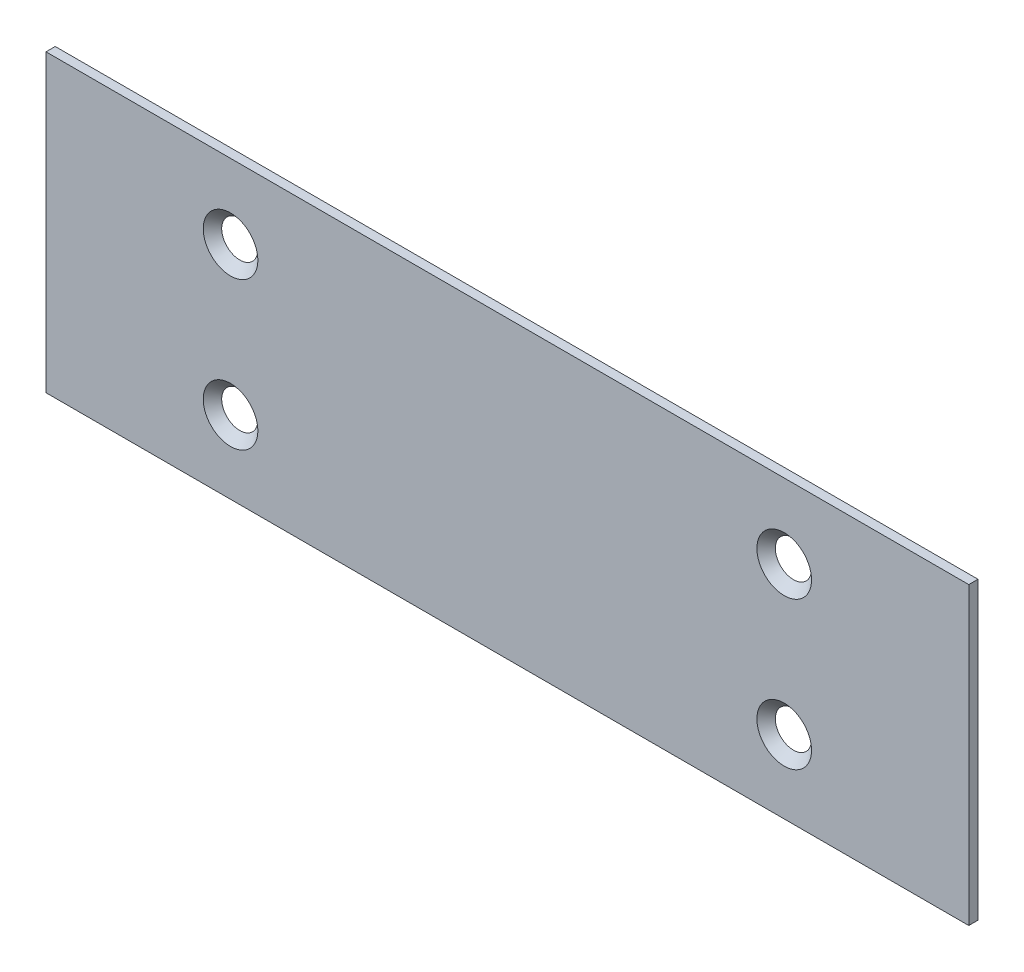
SolidWorks part; units mm, degrees
material "A286 Iron Base Superalloy"
ref_plane "Front Plane" through (0, 0, 0) normal (0, 0, 1) x (1, 0, 0)
ref_plane "Top Plane" through (0, 0, 0) normal (0, 1, 0) x (1, 0, 0)
ref_plane "Right Plane" through (0, 0, 0) normal (1, 0, 0) x (0, 0, -1)
sketch "Sketch1" plane through (0, 0, 0) normal (0, 0, 1) x (1, 0, 0)
  line L1 (0, 0) -> (-158.75, 0)
  line L2 (0, 0) -> (0, 50.8)
  line L3 (0, 50.8) -> (-158.75, 50.8)
  line L4 (-158.75, 0) -> (-158.75, 50.8)
  dimension "D1" = 158.75
  dimension "D2" = 50.8
extrude "Boss-Extrude1" add sketch "Sketch1" along normal blind 1.5875
hole_wizard "CSK for M4 Flat Head Machine Screw1" positions "Sketch3" profile "Sketch2" countersink size "M4" standard "ANSI Metric" end condition through all
sketch "Sketch3" plane through (0, 0, 1.5875) normal (0, 0, 1) x (1, 0, 0)
  line L0 (-158.75, 50.8) -> (-158.75, 0) construction
  line L1 (0, 50.8) -> (-158.75, 50.8) construction
  line L3 (0, 0) -> (0, 50.8) construction
  point P0 (-127, 37.973)
  point P2 (-127, 12.573)
  point P4 (-31.75, 12.573)
  point P6 (-31.75, 37.973)
  dimension "D1" = 31.75
  dimension "D2" = 12.827
  dimension "D3" = 25.4
  dimension "D4" = 31.75
  dimension "D5" = 12.827
  dimension "D6" = 25.4
  dimension "D7" = 31.75
  dimension "D8" = 31.75
sketch "Sketch2" plane through (-127, 37.973, 1.5875) normal (1, 0, 0) x (0, -1, 0)
  line L0 (0, 0) -> (0, 1.5875)
  line L1 (0, 1.5875) -> (2.25, 1.5875)
  line L2 (2.25, 1.5875) -> (2.25, 2.45)
  line L3 (2.25, 2.45) -> (4.7, 0)
  line L5 (4.7, 0) -> (0, 0)
  line L6 (-2.25, 2.45) -> (-4.7, 0) construction
  line L11 (0, -6.35) -> (0, 107.95) construction
  dimension "Thru Hole Dia." = 4.5
  dimension "Thru Hole Depth" = 1.5875
  dimension "Near C'Sink Dia." = 9.4
  dimension "Near C'Sink Angle" = 90
equation "\"D6@Sketch3\"=1"
